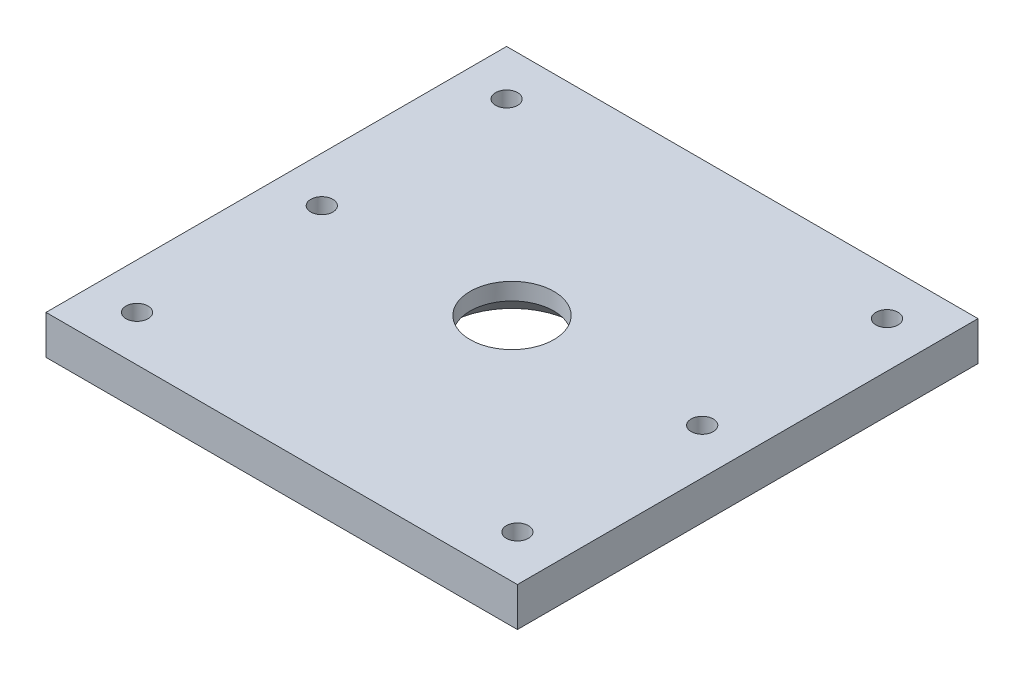
SolidWorks part; units mm, degrees
ref_plane "Front Plane" through (0, 0, 0) normal (0, 0, 1) x (1, 0, 0)
ref_plane "Top Plane" through (0, 0, 0) normal (0, 1, 0) x (1, 0, 0)
ref_plane "Right Plane" through (0, 0, 0) normal (1, 0, 0) x (0, 0, -1)
sketch "Sketch1" plane through (0, 0, 0) normal (0, 1, 0) x (1, 0, 0)
  line L1 (-38.38, -37.5) -> (38.38, -37.5)
  line L2 (-38.38, -37.5) -> (-38.38, 37.5)
  line L3 (-38.38, 37.5) -> (38.38, 37.5)
  line L4 (38.38, -37.5) -> (38.38, 37.5)
  line L5 (-38.38, -37.5) -> (38.38, 37.5) construction
  line L6 (-38.38, 37.5) -> (38.38, -37.5) construction
  point P1 (0, 0)
  dimension "D1" = 76.76
  dimension "D2" = 75
extrude "Boss-Extrude1" add sketch "Sketch1" along normal blind 6.35 contours L1 L4 L3 L2
sketch "Sketch2" plane through (0, 6.35, 0) normal (0, 1, 0) x (1, 0, 0)
  circle A0 centre (0, 0) radius 6.815
  dimension "D1" = 13.63
extrude "Cut-Extrude1" cut sketch "Sketch2" against normal through all
sketch "Sketch3" plane through (0, 6.35, 0) normal (0, 1, 0) x (1, 0, 0)
  line L0 (-38.38, -37.5) -> (-38.38, 37.5) construction
  line L1 (-30.97, -30.09) -> (30.97, -30.09) construction
  line L2 (-30.97, -30.09) -> (-30.97, 30.09) construction
  line L3 (-30.97, 30.09) -> (30.97, 30.09) construction
  line L4 (30.97, -30.09) -> (30.97, 30.09) construction
  line L5 (-30.97, -30.09) -> (30.97, 30.09) construction
  line L6 (-30.97, 30.09) -> (30.97, -30.09) construction
  line L8 (-38.38, 37.5) -> (38.38, 37.5) construction
  circle A0 centre (-30.97, 30.09) radius 1.8
  circle A1 centre (-30.97, -30.09) radius 1.8
  circle A2 centre (30.97, -30.09) radius 1.8
  circle A3 centre (30.97, 30.09) radius 1.8
  circle A4 centre (-30.97, 0) radius 1.8
  circle A5 centre (30.97, 0) radius 1.8
  point P0 (0, 0)
  dimension "D3" = 3.6
  dimension "D1" = 7.41
  dimension "D2" = 7.41
extrude "Cut-Extrude2" cut sketch "Sketch3" against normal through all
chamfer "Chamfer1" distance 3.58 angle 45 1 edges at (0, 0, 6.815)
equation "\"D2@Sketch3\"=\"D1@Sketch3\""
